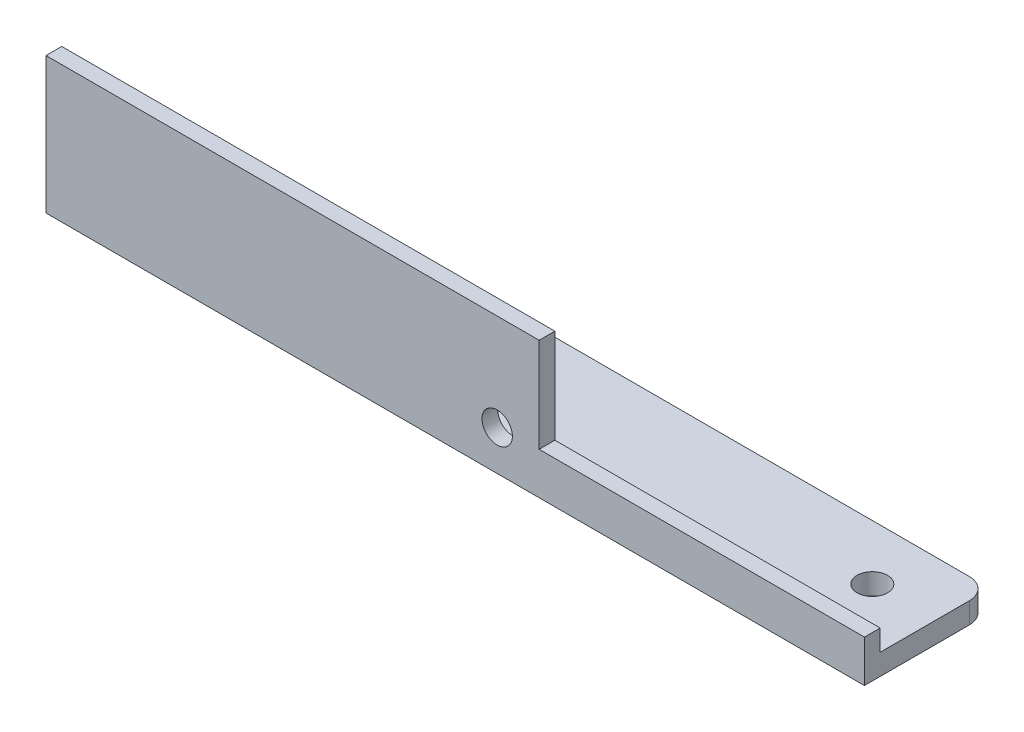
SolidWorks part; units mm, degrees
ref_plane "Plan de face" through (0, 0, 0) normal (0, 0, 1) x (1, 0, 0)
ref_plane "Plan de dessus" through (0, 0, 0) normal (0, 1, 0) x (1, 0, 0)
ref_plane "Plan de droite" through (0, 0, 0) normal (1, 0, 0) x (0, 0, -1)
sketch "Esquisse1" plane through (0, 0, 0) normal (0, 0, 1) x (1, 0, 0)
  line L1 (-39, -6.5) -> (39, -6.5)
  line L2 (-39, -6.5) -> (-39, 6.5)
  line L3 (-39, 6.5) -> (39, 6.5)
  line L4 (39, -6.5) -> (39, 6.5)
  line L5 (-39, -6.5) -> (39, 6.5) construction
  line L6 (-39, 6.5) -> (39, -6.5) construction
  point P0 (0, 0)
  dimension "D1" = 13
  dimension "D2" = 78
extrude "Boss.-Extru.1" add sketch "Esquisse1" along normal blind 12
sketch "Esquisse2" plane through (0, 6.5, 0) normal (0, 1, 0) x (1, 0, 0)
  line L0 (-39, -12) -> (-39, 0) construction
  line L1 (-39, -10.5) -> (39, -10.5)
  line L2 (-39, -10.5) -> (-39, 0)
  line L3 (-39, 0) -> (39, 0)
  line L4 (39, -10.5) -> (39, 0)
  line L5 (39, -12) -> (-39, -12) construction
  dimension "D1" = 1.5
extrude "Enlèv. mat.-Extru.1" cut sketch "Esquisse2" against normal blind 11
hole_wizard "Dégagement M2.51" positions "Esquisse4" profile "Esquisse3" hole size "M2.5" standard "Iso" end condition through all
sketch "Esquisse4" plane through (0, -4.5, 0) normal (0, 1, 0) x (1, 0, 0)
  line L0 (33, 0) -> (33, -5.25) construction
  line L1 (39, 0) -> (-39, 0) construction
  line L4 (33, -5.25) -> (33, -10.5) construction
  line L5 (-39, -10.5) -> (39, -10.5) construction
  line L7 (39, -10.5) -> (39, 0) construction
  point P0 (33, -5.25)
  point P2 (-35, -5.25)
  dimension "D1" = 6
  dimension "D2" = 68
sketch "Esquisse3" plane through (33, -4.5, 5.25) normal (1, 0, 0) x (0, 0, 1)
  line L0 (0, 0) -> (0, 2)
  line L1 (0, 2) -> (1.45, 2)
  line L2 (1.45, 2) -> (1.45, 0)
  line L5 (1.45, 0) -> (0, 0)
  line L11 (0, -6.35) -> (0, 107.95) construction
  dimension "Diamètre du perçage jusqu'au prochain" = 2.9
  dimension "Profondeur du perçage jusqu'au prochain" = 2
sketch "Esquisse5" plane through (0, 0, 10.5) normal (0, 0, -1) x (-1, 0, 0)
  line L0 (39, -4.5) -> (-39, -4.5) construction
  line L1 (-39, 6.5) -> (-8, 6.5)
  line L2 (-39, 6.5) -> (-39, -2.5)
  line L3 (-39, -2.5) -> (-8, -2.5)
  line L4 (-8, 6.5) -> (-8, -2.5)
  dimension "D1" = 2
  dimension "D2" = 31
extrude "Enlèv. mat.-Extru.2" cut sketch "Esquisse5" against normal through all
hole_wizard "Dégagement M2.52" positions "Esquisse7" profile "Esquisse6" hole size "M2.5" standard "Iso"
sketch "Esquisse7" plane through (0, 0, 12) normal (0, 0, 1) x (1, 0, 0)
  line L0 (-39, -4.5) -> (39, -4.5) construction
  line L2 (8, -2.5) -> (8, 6.5) construction
  point P0 (4, -2.7)
  dimension "D1" = 1.8
  dimension "D2" = 4
sketch "Esquisse6" plane through (4, -2.7, 12) normal (1, 0, 0) x (0, -1, 0)
  line L0 (0, 0) -> (0, 24.8712)
  line L1 (0, 24.8712) -> (1.45, 24)
  line L2 (1.45, 24) -> (1.45, 0)
  line L5 (1.45, 0) -> (0, 0)
  line L10 (0, 24.8712) -> (-1.45, 24) construction
  line L11 (0, -6.35) -> (0, 107.95) construction
  dimension "Diamètre du perçage" = 2.9
  dimension "Profondeur du perçage" = 24
  dimension "Angle de pointe" = 118
fillet "Congé1" radius 2 1 edges at (39, -5.5, 0)
